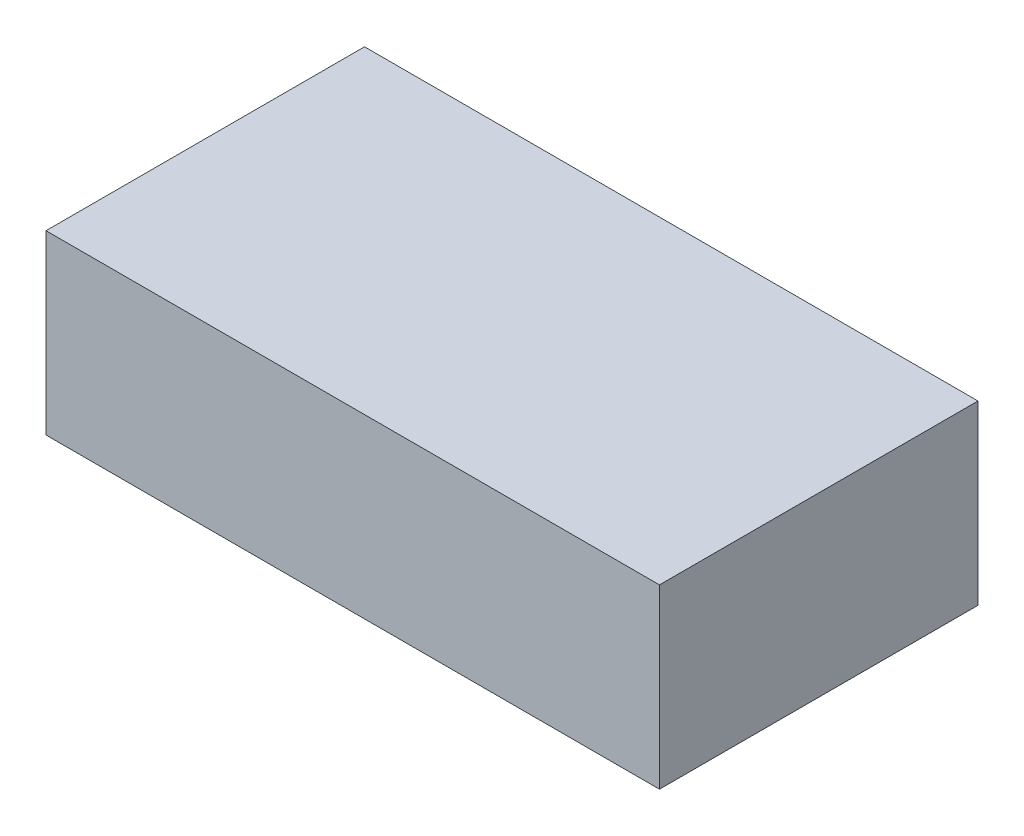
SolidWorks part; units mm, degrees
ref_plane "前视基准面" through (0, 0, 0) normal (0, 0, 1) x (1, 0, 0)
ref_plane "上视基准面" through (0, 0, 0) normal (0, 1, 0) x (1, 0, 0)
ref_plane "右视基准面" through (0, 0, 0) normal (1, 0, 0) x (0, 0, -1)
sketch "草图1" plane through (0, 0, 0) normal (0, 1, 0) x (1, 0, 0)
  line L1 (0, 0) -> (52, 0)
  line L2 (0, 0) -> (0, -27)
  line L3 (0, -27) -> (52, -27)
  line L4 (52, 0) -> (52, -27)
  dimension "D1" = 52
  dimension "D2" = 27
extrude "凸台-拉伸1" add sketch "草图1" along normal blind 15
